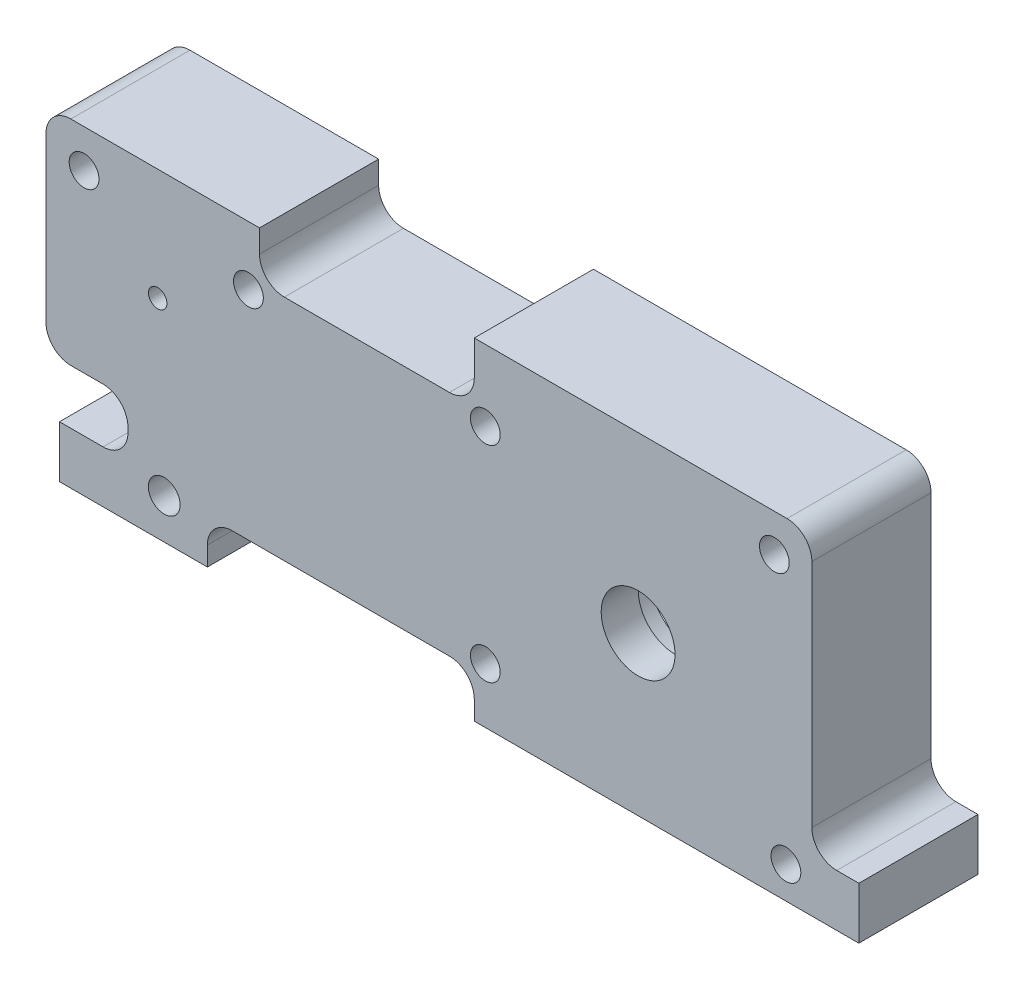
SolidWorks part; units mm, degrees
ref_plane "Front Plane" through (0, 0, 0) normal (0, 0, 1) x (1, 0, 0)
ref_plane "Top Plane" through (0, 0, 0) normal (0, 1, 0) x (1, 0, 0)
ref_plane "Right Plane" through (0, 0, 0) normal (1, 0, 0) x (0, 0, -1)
sketch "Sketch11" plane through (0, 0, 0) normal (0, 0, 1) x (1, 0, 0)
  arc A16 (19.459, 4.3148) -> (4.9137, 3.8376) centre (12.3051, 0.4566) ccw
  arc A17 (4.9137, 3.8376) -> (-9.8691, 3.8376) centre (-2.4777, 0.4566) ccw
  arc A18 (-9.8691, 3.8376) -> (-22.1638, 6.939) centre (-17.2605, 0.4566) ccw
  arc A19 (-22.1638, 6.939) -> (-25.3015, 1.6425) centre (-28.056, 6.8519) ccw
  arc A20 (-25.3015, 1.6425) -> (-9.8691, -2.9245) centre (-17.2605, 0.4566) ccw
  arc A21 (-9.8691, -2.9245) -> (4.9137, -2.9245) centre (-2.4777, 0.4566) ccw
  arc A22 (4.9137, -2.9245) -> (19.459, -3.4017) centre (12.3051, 0.4566) ccw
  arc A23 (19.459, -3.4017) -> (19.459, 4.3148) centre (33.3871, 0.4566) ccw
sketch "Sketch12" plane through (0, 0, 0) normal (0, 0, 1) x (1, 0, 0)
  line L0 (46.0871, 16.3316) -> (20.6871, 16.3316)
  line L1 (49.2621, -12.2434) -> (49.2621, 13.1566)
  line L2 (17.5121, 9.9816) -> (-20.1185, 9.9816)
  line L3 (20.4331, 0.4566) -> (18.9345, 0.4566) construction
  line L4 (-23.2935, 14.7894) -> (-32.8185, 14.7894)
  line L5 (12.3051, 0.4566) -> (-2.4777, 0.4566) construction
  line L6 (-35.9935, 2.0894) -> (-35.9935, 11.6144)
  line L7 (-26.7855, -1.0856) -> (-32.8185, -1.0856)
  line L8 (17.5121, -9.0684) -> (-23.6105, -9.0684)
  line L9 (46.0871, -15.4184) -> (20.6871, -15.4184)
  line L10 (17.5121, 13.1566) -> (17.5121, 9.9816)
  line L12 (17.5121, -9.0684) -> (17.5121, -12.2434)
  line L13 (-20.1185, 9.9816) -> (-20.1185, 11.6144)
  line L15 (-26.7855, -1.0856) -> (-26.7855, -5.8934)
  circle A0 centre (12.3051, 0.4566) radius 9.525 construction
  arc A2 (-20.5385, 9.3997) -> (-20.1185, 9.5427) centre (-17.2605, 0.4566) ccw construction
  circle A3 centre (-2.4777, 0.4566) radius 9.525 construction
  arc A4 (46.0871, 16.3316) -> (49.2621, 13.1566) centre (46.0871, 13.1566) cw
  arc A5 (49.2621, -12.2434) -> (46.0871, -15.4184) centre (46.0871, -12.2434) cw
  arc A6 (17.5121, -12.2434) -> (20.6871, -15.4184) centre (20.6871, -12.2434) ccw
  circle A7 centre (-28.056, 6.8519) radius 7.9375 construction
  arc A8 (17.5121, 13.1566) -> (20.6871, 16.3316) centre (20.6871, 13.1566) cw
  arc A9 (-20.1185, 11.6144) -> (-23.2935, 14.7894) centre (-23.2935, 11.6144) ccw
  arc A10 (-32.8185, 14.7894) -> (-35.9935, 11.6144) centre (-32.8185, 11.6144) ccw
  arc A11 (-32.8185, -1.0856) -> (-35.9935, 2.0894) centre (-32.8185, 2.0894) cw
  arc A12 (-26.7855, -5.8934) -> (-23.6105, -9.0684) centre (-23.6105, -5.8934) ccw
  circle A14 centre (33.3871, 0.4566) radius 15.875 construction
sketch "Sketch4" plane through (0, 0, 0) normal (0, 0, 1) x (1, 0, 0)
  line L0 (-42.3435, -2.9906) -> (-42.3435, 17.9644)
  line L1 (-40.6186, -19.7615) -> (-21.7055, -19.7615)
  line L2 (12.4321, -17.3234) -> (12.4321, -19.7615)
  line L3 (-15.0385, 21.1394) -> (-39.1685, 21.1394)
  line L4 (55.6121, -9.9457) -> (55.6121, 19.5066)
  line L5 (61.6185, -19.7615) -> (61.6185, -13.1207)
  line L6 (61.6185, -13.1207) -> (58.7871, -13.1207)
  line L7 (-40.6186, -19.7615) -> (-40.6186, -13.1207)
  line L8 (-40.6186, -13.1207) -> (-35.0405, -13.1207)
  line L9 (-18.5305, -14.1484) -> (9.2571, -14.1484)
  line L10 (12.4321, 18.2366) -> (12.4321, 22.6816)
  line L11 (-21.7055, -17.3234) -> (-21.7055, -19.7615)
  line L12 (12.4321, -19.7615) -> (61.6185, -19.7615)
  line L13 (9.2571, 15.0616) -> (-11.8635, 15.0616)
  line L14 (-15.0385, 18.2366) -> (-15.0385, 21.1394)
  line L15 (52.4371, 22.6816) -> (12.4321, 22.6816)
  line L16 (-39.1685, -6.1656) -> (-35.0405, -6.1656)
  line L17 (-31.8655, -9.3406) -> (-31.8655, -9.9457)
  line L18 (49.2621, -12.2434) -> (49.2621, 13.1566) construction
  line L19 (46.0871, 16.3316) -> (20.6871, 16.3316) construction
  line L20 (17.5121, 13.1566) -> (17.5121, 9.9816) construction
  line L21 (17.5121, 9.9816) -> (-20.1185, 9.9816) construction
  line L22 (-20.1185, 9.9816) -> (-20.1185, 11.6144) construction
  line L23 (-35.9935, 2.0894) -> (-35.9935, 11.6144) construction
  line L25 (-23.2935, 14.7894) -> (-32.8185, 14.7894) construction
  line L26 (-26.7855, -1.0856) -> (-32.8185, -1.0856) construction
  line L27 (-26.7855, -1.0856) -> (-26.7855, -5.8934) construction
  line L28 (17.5121, -9.0684) -> (-23.6105, -9.0684) construction
  line L29 (17.5121, -9.0684) -> (17.5121, -12.2434) construction
  arc A0 (-39.1685, 21.1394) -> (-42.3435, 17.9644) centre (-39.1685, 17.9644) ccw
  arc A1 (-42.3435, -2.9906) -> (-39.1685, -6.1656) centre (-39.1685, -2.9906) ccw
  arc A2 (-31.8655, -9.3406) -> (-35.0405, -6.1656) centre (-35.0405, -9.3406) ccw
  arc A3 (-31.8655, -9.9457) -> (-35.0405, -13.1207) centre (-35.0405, -9.9457) cw
  arc A4 (-18.5305, -14.1484) -> (-21.7055, -17.3234) centre (-18.5305, -17.3234) ccw
  arc A5 (12.4321, -17.3234) -> (9.2571, -14.1484) centre (9.2571, -17.3234) ccw
  arc A6 (55.6121, -9.9457) -> (58.7871, -13.1207) centre (58.7871, -9.9457) ccw
  arc A7 (55.6121, 19.5066) -> (52.4371, 22.6816) centre (52.4371, 19.5066) ccw
  arc A8 (12.4321, 18.2366) -> (9.2571, 15.0616) centre (9.2571, 18.2366) cw
  arc A9 (-11.8635, 15.0616) -> (-15.0385, 18.2366) centre (-11.8635, 18.2366) cw
  dimension "D3" = 6.35
  dimension "D4" = 5.08
  dimension "D2" = 6.35
  dimension "D14" = 3.175
  dimension "D15" = 3.175
  dimension "D1" = 19.7615
  dimension "D5" = 5.08
  dimension "D6" = 5.08
  dimension "D7" = 6.35
  dimension "D8" = 6.35
  dimension "D9" = 5.08
  dimension "D10" = 5.08
  dimension "D11" = 5.08
  dimension "D12" = 5.08
  dimension "D13" = 5.08
extrude "Extrude3" add sketch "Sketch4" along normal blind 15.24 separate body
sketch "Sketch6" plane through (0, 0, 0) normal (0, 1, 0) x (1, 0, 0)
  line L0 (-37.8295, 0) -> (-37.8295, -25.6603) construction
  line L1 (-35.0405, 0) -> (-40.6186, 0) construction
  line L2 (-29.4475, -3.81) -> (79.3394, -3.81) construction
  line L3 (60.2028, 0) -> (60.2028, -18.8958) construction
  line L4 (61.6185, 0) -> (58.7871, 0) construction
  line L5 (-40.6186, -7.62) -> (81.1858, -7.62) construction
  line L6 (-40.6186, -15.24) -> (-40.6186, 0) construction
  circle A0 centre (-30.1395, 6.985) radius 1.905
  circle A1 centre (60.5909, 6.985) radius 1.905
  circle A2 centre (60.5909, -22.225) radius 1.905
  circle A3 centre (-30.1395, -22.225) radius 1.905
  dimension "D2" = 3.81
  dimension "D1" = 3.81
sketch "Sketch13" plane through (0, 0, 0) normal (0, 0, 1) x (1, 0, 0)
  line L24 (46.0871, 16.3316) -> (20.6871, 16.3316)
  line L25 (49.2621, -12.2434) -> (49.2621, 13.1566)
  line L26 (20.6871, -15.4184) -> (46.0871, -15.4184)
  line L27 (17.5121, -9.0684) -> (17.5121, -12.2434)
  line L28 (-23.6105, -9.0684) -> (17.5121, -9.0684)
  line L29 (-26.7855, -1.0856) -> (-26.7855, -5.8934)
  line L30 (-32.8185, -1.0856) -> (-26.7855, -1.0856)
  line L31 (-35.9935, 11.6144) -> (-35.9935, 2.0894)
  line L32 (-23.2935, 14.7894) -> (-32.8185, 14.7894)
  line L33 (-20.1185, 9.9816) -> (-20.1185, 11.6144)
  line L34 (17.5121, 9.9816) -> (-20.1185, 9.9816)
  line L35 (17.5121, 13.1566) -> (17.5121, 9.9816)
  arc A16 (49.2621, 13.1566) -> (46.0871, 16.3316) centre (46.0871, 13.1566) ccw
  arc A17 (46.0871, -15.4184) -> (49.2621, -12.2434) centre (46.0871, -12.2434) ccw
  arc A18 (17.5121, -12.2434) -> (20.6871, -15.4184) centre (20.6871, -12.2434) ccw
  arc A19 (-26.7855, -5.8934) -> (-23.6105, -9.0684) centre (-23.6105, -5.8934) ccw
  arc A20 (-35.9935, 2.0894) -> (-32.8185, -1.0856) centre (-32.8185, 2.0894) ccw
  arc A21 (-32.8185, 14.7894) -> (-35.9935, 11.6144) centre (-32.8185, 11.6144) ccw
  arc A22 (-20.1185, 11.6144) -> (-23.2935, 14.7894) centre (-23.2935, 11.6144) ccw
  arc A23 (20.6871, 16.3316) -> (17.5121, 13.1566) centre (20.6871, 13.1566) ccw
sketch "Sketch1" plane through (0, 0, 0) normal (0, 0, 1) x (1, 0, 0)
  line L12 (-35.9935, 11.6144) -> (-35.9935, 2.0894)
  line L13 (-23.2935, 14.7894) -> (-32.8185, 14.7894)
  line L14 (-20.1185, 9.9816) -> (-20.1185, 11.6144)
  line L15 (17.5121, 9.9816) -> (-20.1185, 9.9816)
  line L16 (17.5121, 13.1566) -> (17.5121, 9.9816)
  line L17 (46.0871, 16.3316) -> (20.6871, 16.3316)
  line L18 (49.2621, -12.2434) -> (49.2621, 13.1566)
  line L19 (20.6871, -15.4184) -> (46.0871, -15.4184)
  line L20 (17.5121, -9.0684) -> (17.5121, -12.2434)
  line L21 (-23.6105, -9.0684) -> (17.5121, -9.0684)
  line L22 (-26.7855, -1.0856) -> (-26.7855, -5.8934)
  line L23 (-32.8185, -1.0856) -> (-26.7855, -1.0856)
  line L24 (-35.9935, 11.6144) -> (-35.9935, 2.0894)
  line L25 (-23.2935, 14.7894) -> (-32.8185, 14.7894)
  line L26 (-20.1185, 9.9816) -> (-20.1185, 11.6144)
  line L27 (17.5121, 9.9816) -> (-20.1185, 9.9816)
  line L28 (17.5121, 13.1566) -> (17.5121, 9.9816)
  line L29 (46.0871, 16.3316) -> (20.6871, 16.3316)
  line L30 (49.2621, -12.2434) -> (49.2621, 13.1566)
  line L31 (20.6871, -15.4184) -> (46.0871, -15.4184)
  line L32 (17.5121, -9.0684) -> (17.5121, -12.2434)
  line L33 (-23.6105, -9.0684) -> (17.5121, -9.0684)
  line L34 (-26.7855, -1.0856) -> (-26.7855, -5.8934)
  line L35 (-32.8185, -1.0856) -> (-26.7855, -1.0856)
  arc A11 (-35.9935, 2.0894) -> (-32.8185, -1.0856) centre (-32.8185, 2.0894) ccw
  arc A12 (-32.8185, 14.7894) -> (-35.9935, 11.6144) centre (-32.8185, 11.6144) ccw
  arc A13 (-20.1185, 11.6144) -> (-23.2935, 14.7894) centre (-23.2935, 11.6144) ccw
  arc A14 (20.6871, 16.3316) -> (17.5121, 13.1566) centre (20.6871, 13.1566) ccw
  arc A15 (49.2621, 13.1566) -> (46.0871, 16.3316) centre (46.0871, 13.1566) ccw
  arc A16 (46.0871, -15.4184) -> (49.2621, -12.2434) centre (46.0871, -12.2434) ccw
  arc A17 (17.5121, -12.2434) -> (20.6871, -15.4184) centre (20.6871, -12.2434) ccw
  arc A18 (-26.7855, -5.8934) -> (-23.6105, -9.0684) centre (-23.6105, -5.8934) ccw
  arc A19 (-35.9935, 2.0894) -> (-32.8185, -1.0856) centre (-32.8185, 2.0894) ccw
  arc A20 (-32.8185, 14.7894) -> (-35.9935, 11.6144) centre (-32.8185, 11.6144) ccw
  arc A21 (-20.1185, 11.6144) -> (-23.2935, 14.7894) centre (-23.2935, 11.6144) ccw
  arc A22 (20.6871, 16.3316) -> (17.5121, 13.1566) centre (20.6871, 13.1566) ccw
  arc A23 (49.2621, 13.1566) -> (46.0871, 16.3316) centre (46.0871, 13.1566) ccw
  arc A24 (46.0871, -15.4184) -> (49.2621, -12.2434) centre (46.0871, -12.2434) ccw
  arc A25 (17.5121, -12.2434) -> (20.6871, -15.4184) centre (20.6871, -12.2434) ccw
  arc A26 (-26.7855, -5.8934) -> (-23.6105, -9.0684) centre (-23.6105, -5.8934) ccw
  dimension "D1" = 0
extrude "Extrude4" cut sketch "Sketch1" along normal blind 6.477
sketch "Sketch7" plane through (0, 0, 6.477) normal (0, 0, -1) x (-1, 0, 0)
  circle A0 centre (-33.3871, 0.4566) radius 7.8994
  dimension "D1" = 15.7988
extrude "Extrude5" cut sketch "Sketch7" against normal blind 4.0132
sketch "Sketch8" plane through (0, 0, 6.477) normal (0, 0, -1) x (-1, 0, 0)
  circle A0 centre (-12.3051, 0.4566) radius 2.2987
  circle A1 centre (2.4777, 0.4566) radius 2.2987
  circle A2 centre (17.2605, 0.4566) radius 2.2987
  dimension "D1" = 4.5974
extrude "Extrude6" cut sketch "Sketch8" against normal blind 4.2926
sketch "Sketch9" plane through (0, 0, 6.477) normal (0, 0, -1) x (-1, 0, 0)
  circle A0 centre (28.056, 6.8519) radius 4.4196
  dimension "D1" = 8.8392
extrude "Extrude7" cut sketch "Sketch9" against normal blind 4.4196
sketch "Sketch10" plane through (0, 0, 10.4902) normal (0, 0, -1) x (-1, 0, 0)
  line L0 (-33.3871, 0.4566) -> (-54.6821, 21.7516) construction
  line L2 (-52.2874, 19.3569) -> (-52.2874, -15.6781) construction
  line L3 (11.8635, 18.2366) -> (-9.2571, 18.2366) construction
  line L4 (-9.2571, 18.2366) -> (1.3032, 23.5942) construction
  line L5 (1.3032, 23.5942) -> (1.3032, -17.7894) construction
  line L6 (2.4777, 0.4566) -> (-12.3051, 0.4566) construction
  line L7 (28.056, 6.8519) -> (41.4135, 20.2095) construction
  circle A0 centre (-33.3871, 0.4566) radius 4.7244
  circle A2 centre (-52.2874, -15.6781) radius 1.905
  circle A4 centre (28.056, 6.8519) radius 1.1793
  circle A5 centre (37.4743, 16.2702) radius 1.905
  circle A6 centre (-13.8463, 13.5969) radius 1.905
  circle A7 centre (-13.8463, -12.6838) radius 1.905
  arc A8 (-52.4371, 22.6816) -> (-55.6121, 19.5066) centre (-52.4371, 19.5066) ccw construction
  arc A9 (42.3435, 17.9644) -> (39.1685, 21.1394) centre (39.1685, 17.9644) ccw construction
  circle A10 centre (27.2212, -14.6226) radius 2.032
  circle A11 centre (-50.815, 17.8845) radius 1.905
  circle A12 centre (16.4527, 13.5969) radius 1.905
  dimension "D1" = 9.4488
  dimension "D2" = 3.81
extrude "Extrude8" cut sketch "Sketch10" against normal mid plane 35.1536
